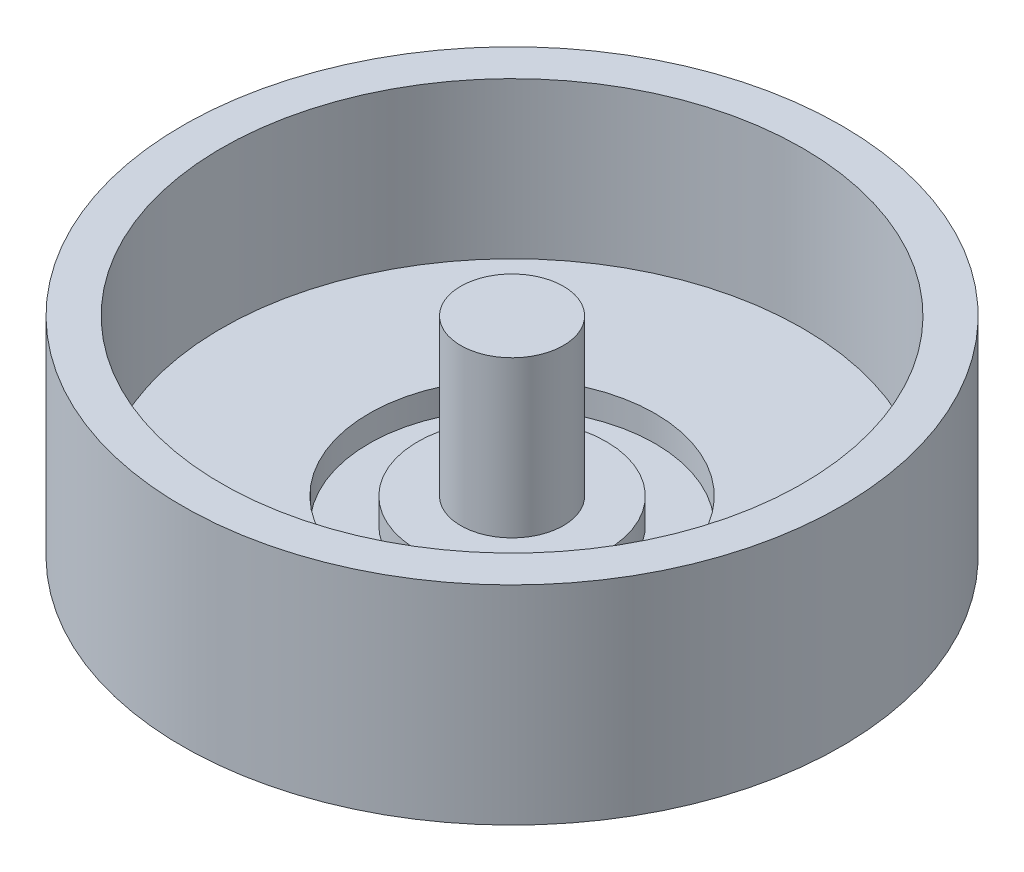
SolidWorks part; units mm, degrees
ref_plane "Top Plane" through (0, 0, 0) normal (0, 0, 1) x (1, 0, 0)
ref_plane "Right Plane" through (0, 0, 0) normal (0, 1, 0) x (1, 0, 0)
ref_plane "Front Plane" through (0, 0, 0) normal (1, 0, 0) x (0, 0, -1)
sketch "Sketch1" plane through (0, 0, 0) normal (1, 0, 0) x (0, 0, -1)
  line L0 (0, 0) -> (0, 16)
  line L1 (0, 16) -> (3.95, 16)
  line L2 (3.95, 16) -> (3.95, 4)
  line L3 (3.95, 4) -> (7.25, 4)
  line L4 (7.25, 4) -> (7.25, 2)
  line L5 (7.25, 2) -> (11, 2)
  line L6 (11, 2) -> (11, 4)
  line L7 (11, 4) -> (22.35, 4)
  line L8 (22.35, 4) -> (22.35, 16)
  line L9 (22.35, 16) -> (25.35, 16)
  line L10 (25.35, 16) -> (25.35, 0)
  line L11 (25.35, 0) -> (0, 0)
  dimension "D1" = 3.95
  dimension "D2" = 7.25
  dimension "D3" = 12
  dimension "D4" = 2
  dimension "D5" = 2
  dimension "D6" = 22.35
  dimension "D7" = 3
  dimension "D8" = 11
  dimension "D9" = 3.75
revolve "Revolve1" add sketch "Sketch1" angle 360 about L0
